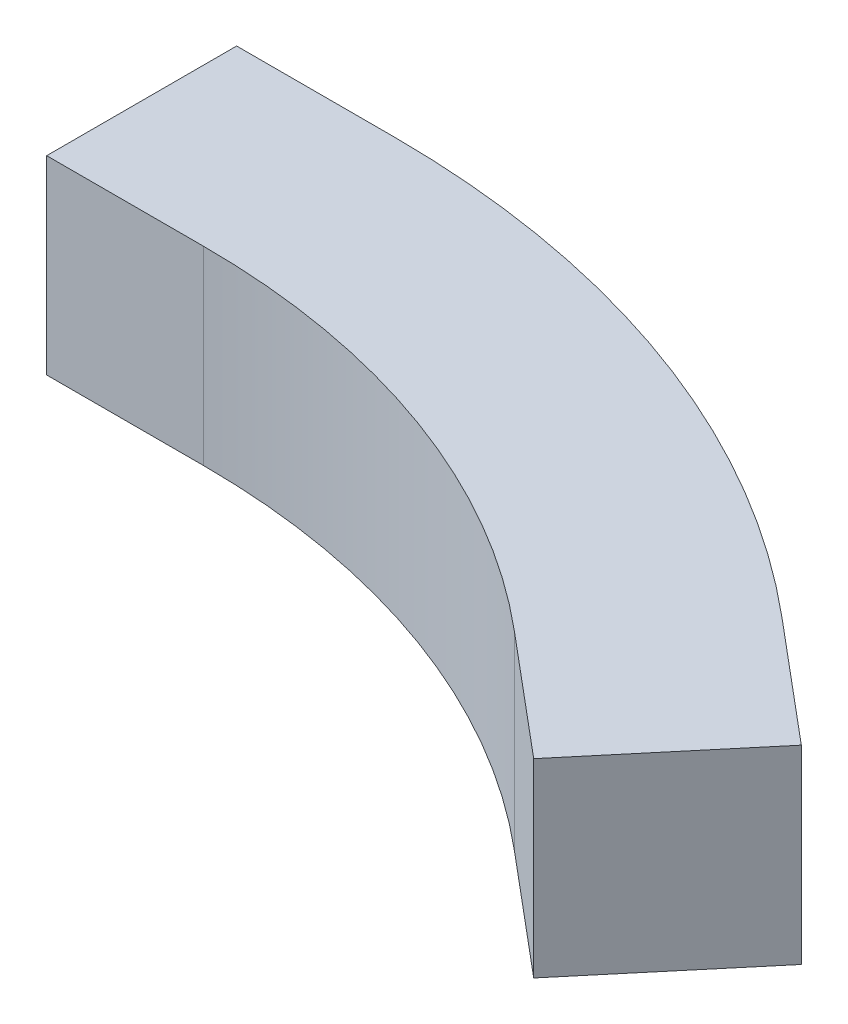
SolidWorks part; units mm, degrees
ref_plane "Front Plane" through (0, 0, 0) normal (0, 0, 1) x (1, 0, 0)
ref_plane "Top Plane" through (0, 0, 0) normal (0, 1, 0) x (1, 0, 0)
ref_plane "Right Plane" through (0, 0, 0) normal (1, 0, 0) x (0, 0, -1)
sketch "Sketch1" plane through (0, 0, 0) normal (0, 1, 0) x (1, 0, 0)
  line L0 (0, 0) -> (0, 75)
  line L1 (0, 0) -> (48.2091, 57.4533)
  line L2 (48.2091, 57.4533) -> (57.708, 49.4828)
  line L3 (0, 75) -> (-12.4, 75)
  line L4 (0, 75) -> (0, 60)
  line L5 (0, 60) -> (-12.4, 60)
  line L6 (-12.4, 75) -> (-12.4, 60)
  line L7 (57.708, 49.4828) -> (48.0662, 37.9921)
  line L8 (48.0662, 37.9921) -> (38.5673, 45.9627)
  circle A0 centre (0, 0) radius 75
  circle A1 centre (0, 0) radius 60
  point P11 (0, 0)
  point P14 (0, 0)
  dimension "D1" = 15
  dimension "D2" = 150
  dimension "D3" = 40
  dimension "D4" = 12.4
extrude "Boss-Extrude1" add sketch "Sketch1" along normal blind 15 contours A1 L1 A0 L0 | L7 A0 L1 L8 | A0 L7 L2 | A0 L3 L6 | L0 A0 L6 L5
